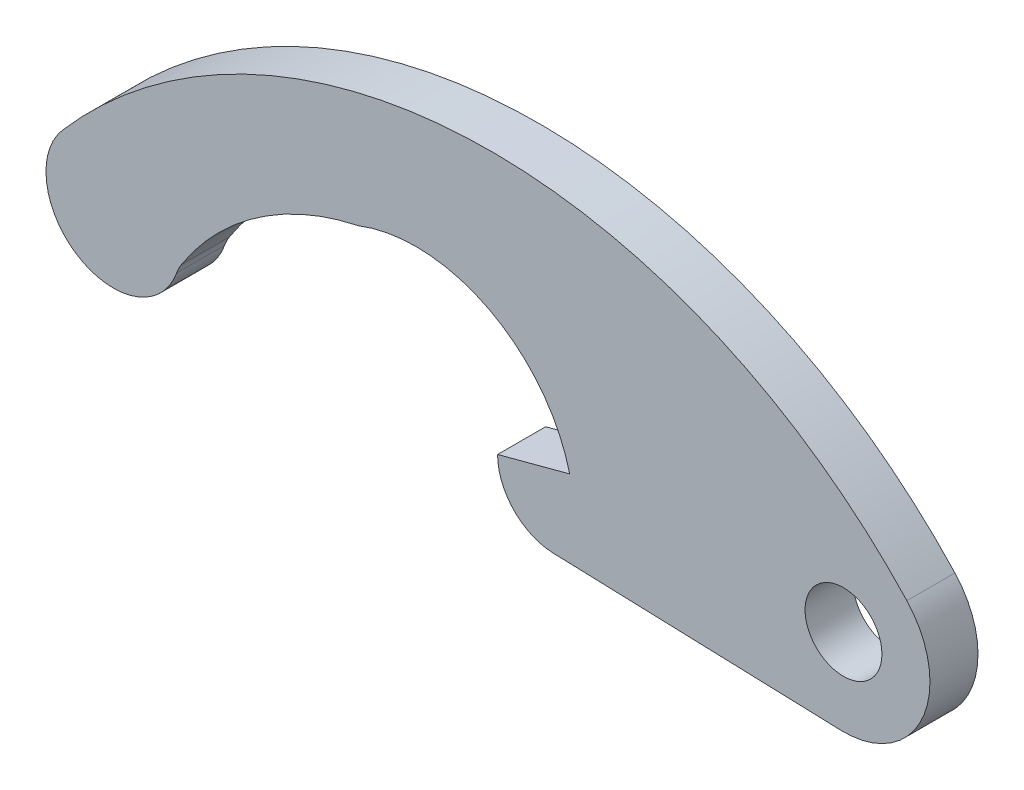
SolidWorks part; units mm, degrees
ref_plane "Front Plane" through (0, 0, 0) normal (0, 0, 1) x (1, 0, 0)
ref_plane "Top Plane" through (0, 0, 0) normal (0, 1, 0) x (1, 0, 0)
ref_plane "Right Plane" through (0, 0, 0) normal (1, 0, 0) x (0, 0, -1)
sketch "Sketch1" plane through (0, 0, 0) normal (0, 0, 1) x (1, 0, 0)
  line L0 (-49.4148, 25.4) -> (16.3033, 25.4) construction
  line L1 (-49.4148, 27.432) -> (21.1959, 27.432) construction
  line L2 (-49.4148, 27.432) -> (-8.0766, 27.432) construction
  line L3 (-49.4148, 26.416) -> (17.9203, 26.416) construction
  line L4 (-49.4148, 26.416) -> (-8.0766, 26.416) construction
  line L5 (-49.4148, 25.4) -> (-8.0766, 25.4) construction
  line L6 (-18.1357, 23.3697) -> (-2.9466, 22.8625)
  line L7 (-17.268, 27.432) -> (-21.082, 26.416)
  arc A1 (-28.442, 33.2105) -> (-37.8002, 26.7501) centre (-25.4, 18.796) ccw
  arc A2 (-44.0924, 29.7573) -> (-38.0538, 26.2342) centre (-41.402, 27.432) ccw
  arc A3 (-21.082, 26.416) -> (-18.1357, 23.3697) centre (-18.034, 26.416) ccw
  arc A4 (-2.9466, 22.8625) -> (0.558, 30.5412) centre (-2.794, 27.432) ccw
  arc A5 (-17.268, 27.432) -> (-28.442, 33.2105) centre (-25.4, 25.4) ccw
  arc A6 (0.558, 30.5412) -> (-44.0924, 29.7573) centre (-21.4162, 10.1585) ccw
  arc A7 (-37.8002, 26.7501) -> (-38.0538, 26.2342) centre (-35.6622, 25.3787) ccw
  dimension "D4" = 29.464
  dimension "D6" = 7.112
  dimension "D10" = 6.096
  dimension "D12" = 9.144
  dimension "D14" = 8.382
  dimension "D15" = 29.972
  dimension "D16" = 2.54
  dimension "D2" = 25.4
  dimension "D3" = 25.4
  dimension "D5" = 6.604
  dimension "D7" = 16.002
  dimension "D11" = 7.366
  dimension "D13" = 15.24
  dimension "D8" = 2.032
  dimension "D9" = 1.016
extrude "Boss-Extrude1" add sketch "Sketch1" along normal blind 2.54
sketch "Sketch2" plane through (0, 0, 2.54) normal (0, 0, 1) x (1, 0, 0)
  circle A0 centre (-2.794, 27.432) radius 2.032
  arc A1 (-2.9466, 22.8625) -> (0.558, 30.5412) centre (-2.794, 27.432) ccw construction
  dimension "D1" = 4.064
extrude "Cut-Extrude1" cut sketch "Sketch2" against normal through all
